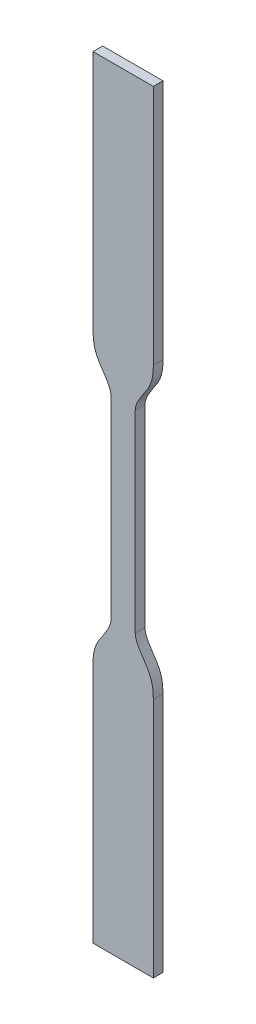
SolidWorks part; units mm, degrees
ref_plane "Front Plane" through (0, 0, 0) normal (0, 0, 1) x (1, 0, 0)
ref_plane "Top Plane" through (0, 0, 0) normal (0, 1, 0) x (1, 0, 0)
ref_plane "Right Plane" through (0, 0, 0) normal (1, 0, 0) x (0, 0, -1)
sketch "Sketch1" plane through (0, 0, 0) normal (0, 0, 1) x (1, 0, 0)
  line L0 (0, 0) -> (0, 101.6) construction
  line L1 (0, 0) -> (0, -101.6) construction
  line L2 (-3.175, 0) -> (3.175, 0) construction
  line L3 (-7.9375, -101.6) -> (7.9375, -101.6)
  line L4 (-7.9375, 101.6) -> (7.9375, 101.6)
  line L5 (3.175, -25.4) -> (3.175, 25.4)
  line L6 (-3.175, -25.4) -> (-3.175, 25.4)
  line L7 (-7.9375, -101.6) -> (-7.9375, -38.1)
  line L9 (7.9375, -101.6) -> (7.9375, -38.1)
  line L10 (0, 31.9007) -> (-6.4516, 31.9007) construction
  line L11 (-7.9375, 101.6) -> (-7.9375, 38.1)
  line L12 (7.9375, 101.6) -> (7.9375, 38.1)
  line L13 (-7.9375, 38.1) -> (-7.9375, 33.1511) construction
  line L15 (-3.175, 25.4) -> (-3.175, 38.1) construction
  line L16 (-3.175, 38.1) -> (-7.9375, 38.1) construction
  spline S0 degree 3 poles (-7.9375, 38.1) (-7.9375, 35.4194) (-7.0851, 31.8967) (-3.2529, 27.6399) (-3.175, 25.4) knots 0 0 0 0 0.475836 1 1 1 1
  spline S1 degree 3 poles (7.9375, 38.1) (7.9375, 35.4194) (7.0851, 31.8967) (3.2529, 27.6399) (3.175, 25.4) knots 0 0 0 0 0.475836 1 1 1 1
  spline S2 degree 3 poles (7.9375, -38.1) (7.9375, -35.4194) (7.0851, -31.8967) (3.2529, -27.6399) (3.175, -25.4) knots 0 0 0 0 0.475836 1 1 1 1
  spline S3 degree 3 poles (-7.9375, -38.1) (-7.9375, -35.4194) (-7.0851, -31.8967) (-3.2529, -27.6399) (-3.175, -25.4) knots 0 0 0 0 0.475836 1 1 1 1
  point P14 (-3.2258, 31.9007)
extrude "Boss-Extrude1" add sketch "Sketch1" along normal blind 2.54
ref_plane "Plane1" through (0, 0, 2.54) normal (0, 0, 1) x (1, 0, 0)
sketch "Sketch2" plane through (0, 0, 2.54) normal (0, 0, 1) x (1, 0, 0)
  line L0 (0, 101.6) -> (0, -101.6) construction
  line L1 (7.9375, 101.6) -> (-7.9375, 101.6) construction
  line L2 (-7.9375, -101.6) -> (7.9375, -101.6) construction
